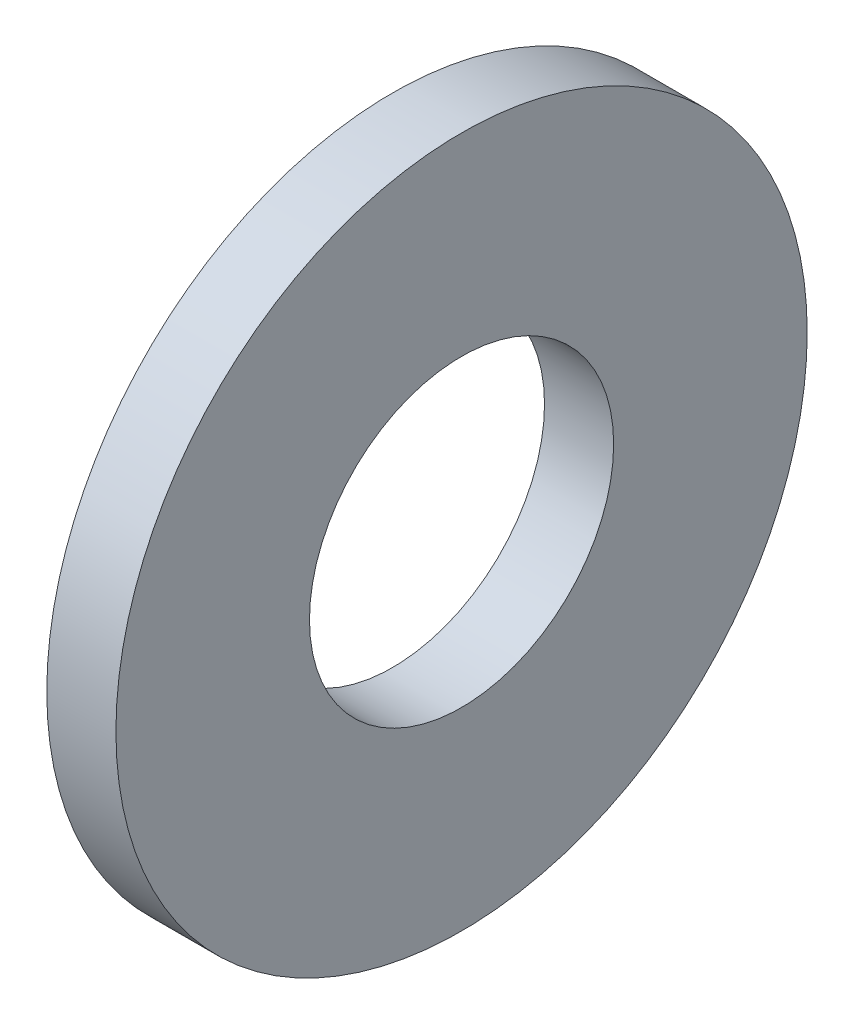
SolidWorks part; units mm, degrees
ref_plane "Plane1" through (0, 0, 0) normal (0, 0, 1) x (1, 0, 0)
ref_plane "Plane2" through (0, 0, 0) normal (0, 1, 0) x (1, 0, 0)
ref_plane "Plane3" through (0, 0, 0) normal (1, 0, 0) x (0, 0, -1)
other "Configuration Table"
sketch "Sketch1" plane through (0, 0, 0) normal (1, 0, 0) x (0, 0, -1)
  circle A0 centre (0, 0) radius 4.4
  circle A1 centre (0, 0) radius 10
  dimension "Insid_dia" = 8.8
  dimension "OutsideDia" = 20
extrude "Base-Extrude" add sketch "Sketch1" along normal blind 2
